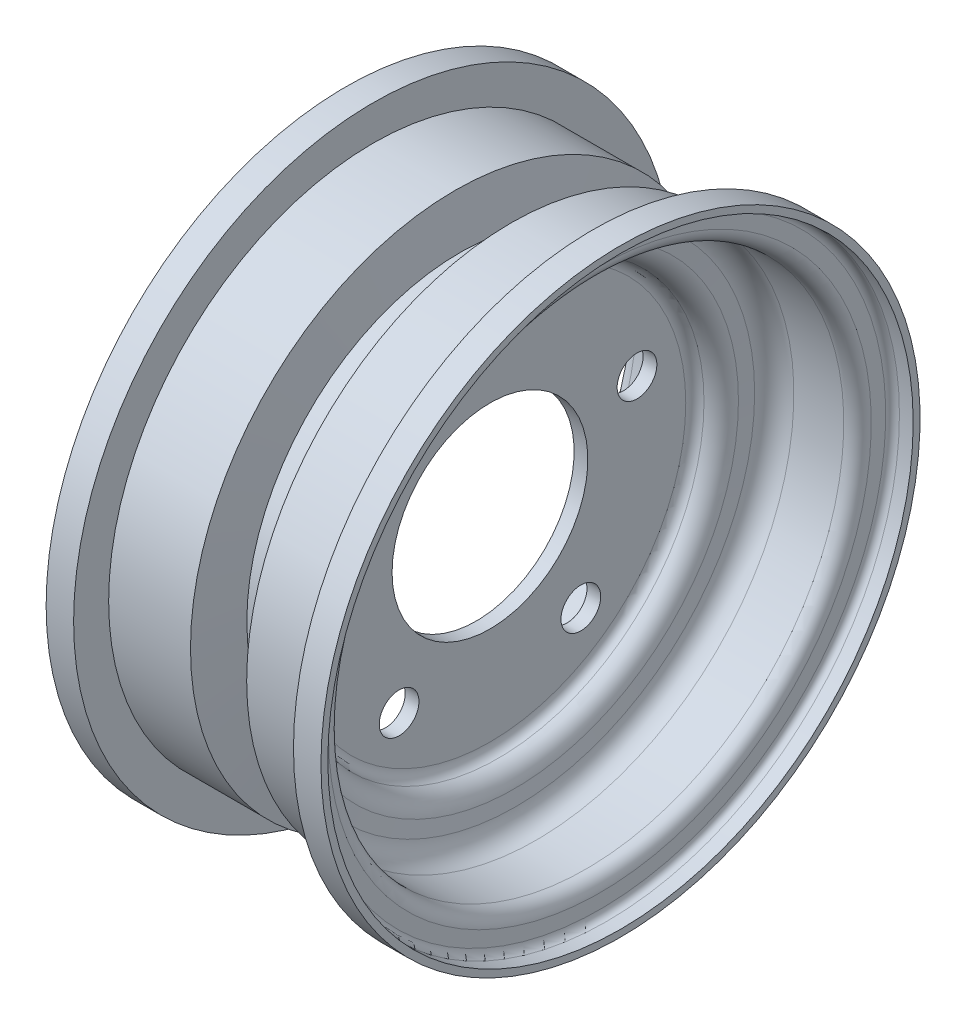
SolidWorks part; units mm, degrees
material "1023 Carbon Steel Sheet (SS)"
ref_plane "Front Plane" through (0, 0, 0) normal (0, 0, 1) x (1, 0, 0)
ref_plane "Top Plane" through (0, 0, 0) normal (0, 1, 0) x (1, 0, 0)
ref_plane "Right Plane" through (0, 0, 0) normal (1, 0, 0) x (0, 0, -1)
sketch "Sketch2" plane through (0, 0, 0) normal (0, 0, 1) x (1, 0, 0)
  line L0 (2.54, 0) -> (2.54, 36.195) construction
  line L1 (2.54, 36.195) -> (2.54, 76.2)
  line L2 (2.54, 76.2) -> (10.922, 76.2)
  line L3 (50.8, 110.744) -> (50.8, 108.204)
  line L4 (12.7, 95.25) -> (43.18, 95.25)
  line L5 (43.18, 95.25) -> (43.18, 108.204)
  line L6 (43.18, 108.204) -> (50.8, 108.204)
  line L7 (10.922, 76.2) -> (12.7, 95.25)
  line L8 (0, 0) -> (2.54, 0) construction
  line L9 (0, 0) -> (0, 213.5492) construction
  line L10 (0, 36.195) -> (0, 78.74)
  line L11 (0, 78.74) -> (8.608, 78.74)
  line L12 (8.608, 78.74) -> (10.386, 97.79)
  line L13 (10.386, 97.79) -> (40.64, 97.79)
  line L14 (40.64, 97.79) -> (40.64, 110.744)
  line L15 (40.64, 110.744) -> (48.26, 110.744)
  line L16 (48.26, 110.744) -> (48.26, 110.744)
  line L17 (0, 36.195) -> (2.54, 36.195)
  line L18 (48.26, 110.744) -> (50.8, 110.744)
  dimension "D1" = 36.195
  dimension "D2" = 76.2
  dimension "D3" = 8.382
  dimension "D4" = 19.05
  dimension "D5" = 2.54
  dimension "D6" = 7.62
  dimension "D7" = 30.48
  dimension "0.51" = 12.954
  dimension "D8" = 2.54
  dimension "D9" = 48.26
  dimension "D10" = 2.54
revolve "Revolve2" add sketch "Sketch2" angle 360 about L8
mirror "Mirror1" about plane through (0, 0, 0) normal (1, 0, 0) of "Revolve2"
sketch "Sketch5" plane through (0, 0, 0) normal (1, 0, 0) x (0, 0, -1)
  line L1 (54.3529, 17.6603) -> (0, 57.15) construction
  line L2 (0, 57.15) -> (-54.3529, 17.6603) construction
  line L8 (-54.3529, 17.6603) -> (-33.5919, -46.2353) construction
  line L9 (-33.5919, -46.2353) -> (33.5919, -46.2353) construction
  line L10 (33.5919, -46.2353) -> (54.3529, 17.6603) construction
  circle A3 centre (0, 0) radius 57.15 construction
  dimension "D1" = 114.3
hole_wizard "37/64 (0.57813) Diameter Hole1" positions "Sketch6" profile "Sketch7" hole size "37/64" standard "ANSI Inch" end condition through all
sketch "Sketch6" plane through (2.54, 0, 0) normal (1, 0, 0) x (0, 0, -1)
  point P0 (0, 57.15)
  point P3 (54.3529, 17.6603)
  point P6 (33.5919, -46.2353)
  point P9 (-33.5919, -46.2353)
  point P12 (-54.3529, 17.6603)
sketch "Sketch7" plane through (2.54, 57.15, 0) normal (0, 1, 0) x (0, 0, -1)
  line L0 (0, 0) -> (0, 53.34)
  line L1 (0, 53.34) -> (7.3423, 53.34)
  line L2 (7.3423, 53.34) -> (7.3423, 0)
  line L5 (7.3423, 0) -> (0, 0)
  line L11 (0, -6.35) -> (0, 107.95) construction
  dimension "Thru Hole Dia." = 14.6845
  dimension "Thru Hole Depth" = 53.34
fillet "Fillet1" radius 3.81 2 edges at (2.54, 0, 76.2) (-2.54, 0, 76.2)
fillet "Fillet2" radius 7.62 4 edges at (12.7, 0, 95.25) (10.922, 0, 76.2) (-12.7, 0, 95.25) (-10.922, 0, 76.2)
fillet "Fillet3" radius 5.08 2 edges at (43.18, 0, 95.25) (-43.18, 0, 95.25)
fillet "Fillet4" radius 2.54 2 edges at (43.18, 0, 108.204) (-43.18, 0, 108.204)
